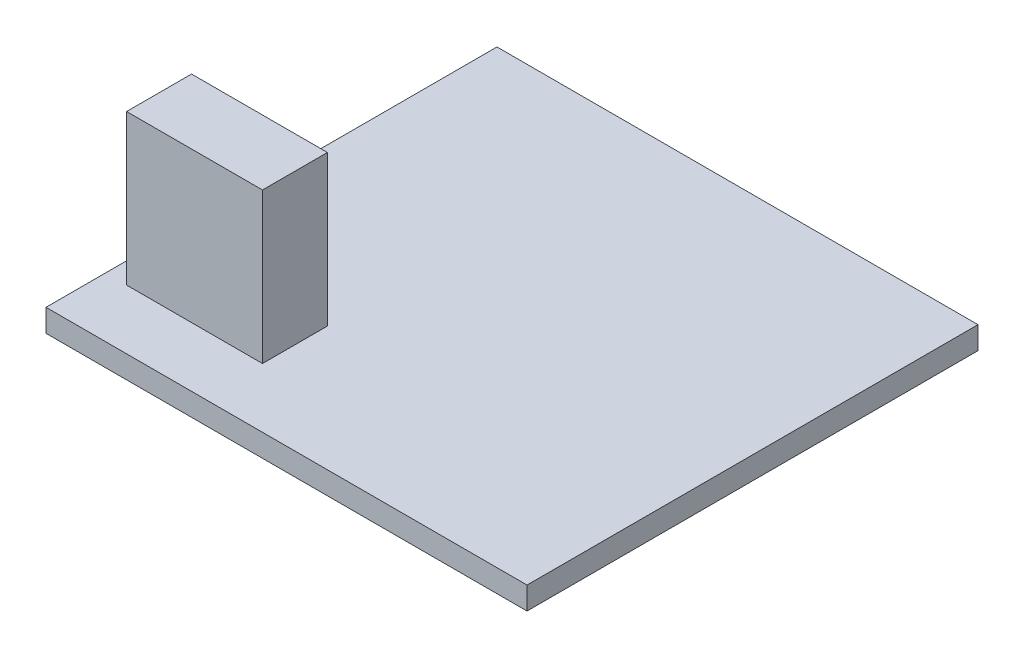
SolidWorks part; units mm, degrees
ref_plane "前视基准面" through (0, 0, 0) normal (0, 0, 1) x (1, 0, 0)
ref_plane "上视基准面" through (0, 0, 0) normal (0, 1, 0) x (1, 0, 0)
ref_plane "右视基准面" through (0, 0, 0) normal (1, 0, 0) x (0, 0, -1)
sketch "草图1" plane through (0, 0, 0) normal (0, 1, 0) x (1, 0, 0)
  line L1 (-16, -15) -> (16, -15)
  line L2 (-16, -15) -> (-16, 15)
  line L3 (-16, 15) -> (16, 15)
  line L4 (16, -15) -> (16, 15)
  line L5 (-16, -15) -> (16, 15) construction
  line L6 (-16, 15) -> (16, -15) construction
  point P0 (0, 0)
  dimension "D1" = 32
  dimension "D2" = 30
extrude "凸台-拉伸1" add sketch "草图1" along normal blind 1.5
sketch "草图2" plane through (0, 1.5, 0) normal (0, 1, 0) x (1, 0, 0)
  line L1 (-14.5989, -6.7195) -> (-5.5596, -6.7195)
  line L2 (-14.5989, -6.7195) -> (-14.5989, -11.0392)
  line L3 (-14.5989, -11.0392) -> (-5.5596, -11.0392)
  line L4 (-5.5596, -6.7195) -> (-5.5596, -11.0392)
  line L5 (-14.5989, -6.7195) -> (-5.5596, -11.0392) construction
  line L6 (-14.5989, -11.0392) -> (-5.5596, -6.7195) construction
  point P0 (-10.0793, -8.8794)
extrude "凸台-拉伸2" add sketch "草图2" along normal blind 10 contours L2 L1 L4 L3
